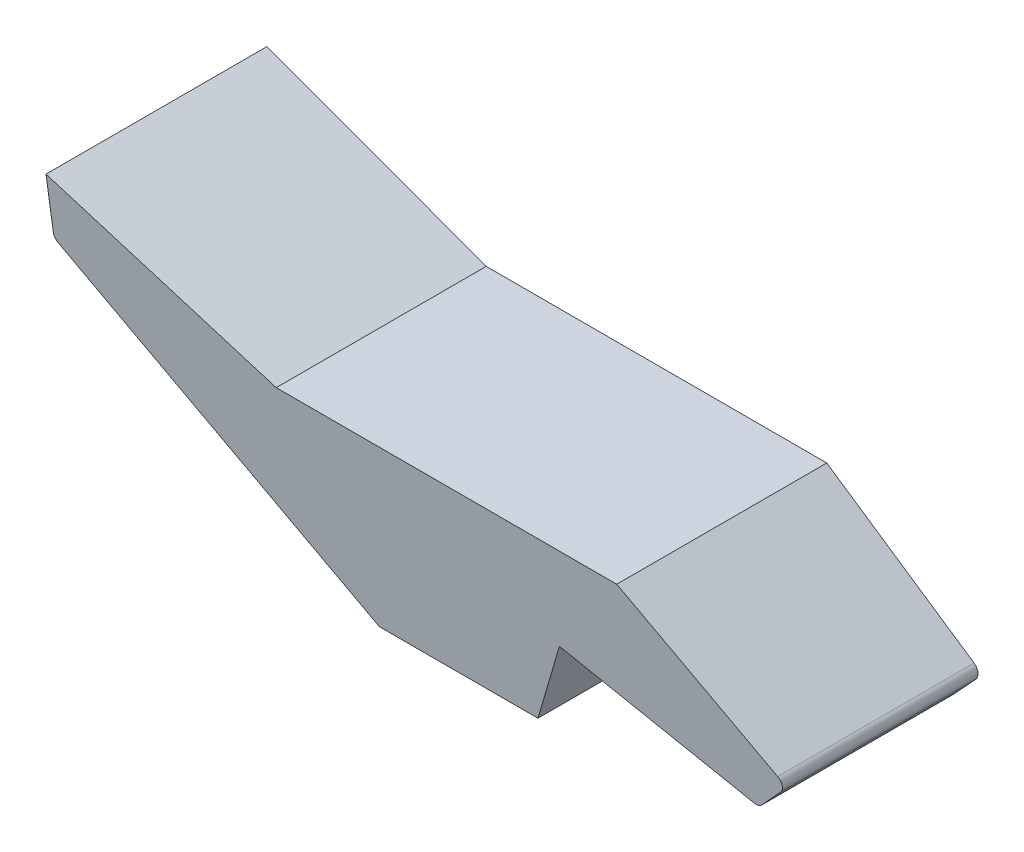
SolidWorks part; units mm, degrees
ref_plane "Front Plane" through (0, 0, 0) normal (0, 0, 1) x (1, 0, 0)
ref_plane "Top Plane" through (0, 0, 0) normal (0, 1, 0) x (1, 0, 0)
ref_plane "Right Plane" through (0, 0, 0) normal (1, 0, 0) x (0, 0, -1)
sketch "Sketch1" plane through (0, 0, 0) normal (0, 0, 1) x (1, 0, 0)
  line L0 (357.0595, 173.035) -> (357.0595, 163.2618)
  line L1 (357.7578, 161.9467) -> (410.5841, 126.2266)
  line L2 (410.5841, 126.2266) -> (439.064, 126.2266)
  line L3 (439.064, 126.2266) -> (444.9781, 141.3909)
  line L4 (444.9781, 141.3909) -> (478.8199, 133.4468)
  line L5 (480.3494, 133.9156) -> (484.3447, 138.2449)
  line L6 (484.0673, 140.6366) -> (457.6039, 158.5306)
  line L7 (457.6039, 158.5306) -> (396.4403, 158.5306)
  line L8 (396.4403, 158.5306) -> (357.0595, 173.035)
  arc A0 (357.0595, 163.2618) -> (357.7578, 161.9467) centre (358.647, 163.2618) ccw
  arc A1 (484.3447, 138.2449) -> (484.0673, 140.6366) centre (483.178, 139.3215) ccw
  arc A2 (478.8199, 133.4468) -> (480.3494, 133.9156) centre (479.1827, 134.9923) ccw
  dimension "D1" = 1.5875
extrude "Boss-Extrude1" add sketch "Sketch1" along normal blind 20.6375 and the other way blind 19.05 contours L6 L7 L8 L0 A0 L1 L2 L3 L4 A2 L5 A1
sketch "Sketch2" plane through (0, 126.2266, 0) normal (0, -1, 0) x (1, 0, 0)
  line L0 (410.5841, 14.2875) -> (439.064, 14.2875)
  line L1 (410.5841, -19.05) -> (410.5841, 20.6375) construction
  line L2 (439.064, -19.05) -> (439.064, 20.6375) construction
  line L3 (410.5841, 20.6375) -> (439.064, 20.6375) construction
  dimension "D1" = 6.35
ref_plane "Plane1" through (0, 0.3778, -2.785) normal (0, -0.1344, 0.9909) x (1, 0, 0)
sketch "Sketch3" plane through (0, 0.3778, -2.785) normal (0, -0.1344, 0.9909) x (1, 0, 0)
  line L1 (350.0272, 179.7538) -> (499.5813, 179.7538)
  line L2 (350.0272, 179.7538) -> (350.0272, 105.2716)
  line L3 (350.0272, 105.2716) -> (499.5813, 105.2716)
  line L4 (499.5813, 179.7538) -> (499.5813, 105.2716)
extrude "Cut-Extrude1" cut sketch "Sketch3" along normal through all
